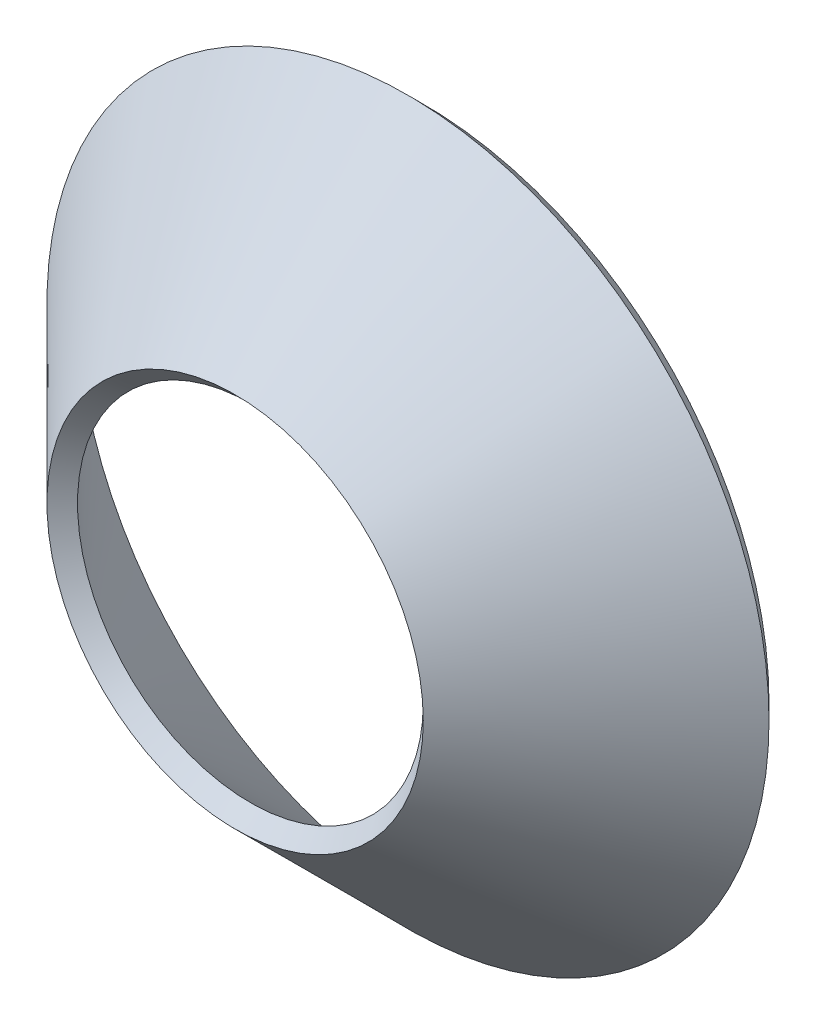
SolidWorks part; units mm, degrees
ref_plane "Front Plane" through (0, 0, 0) normal (1, 0, 0) x (0, 1, 0)
ref_plane "Top Plane" through (0, 0, 0) normal (0, 0, 1) x (0, 1, 0)
ref_plane "Right Plane" through (0, 0, 0) normal (0, 1, 0) x (-1, 0, 0)
sketch "Sketch1" plane through (0, 0, 0) normal (1, 0, 0) x (0, 1, 0)
  line L0 (25.4, 25.4) -> (50.8, 0)
  line L1 (13.8471, 0) -> (-13.8471, 0) construction
  line L2 (0, -13.8471) -> (0, 13.8471) construction
  dimension "D1" = 45
  dimension "D2" = 25.4
  dimension "D3" = 25.4
ref_axis "Axis1" through (0, 0, 26.67) along (0, 0, -1)
revolve "Revolve-Thin1" add sketch "Sketch1" angle 360 about axis through (0, 0, 26.67) along (0, 0, -1) wall 3.175
